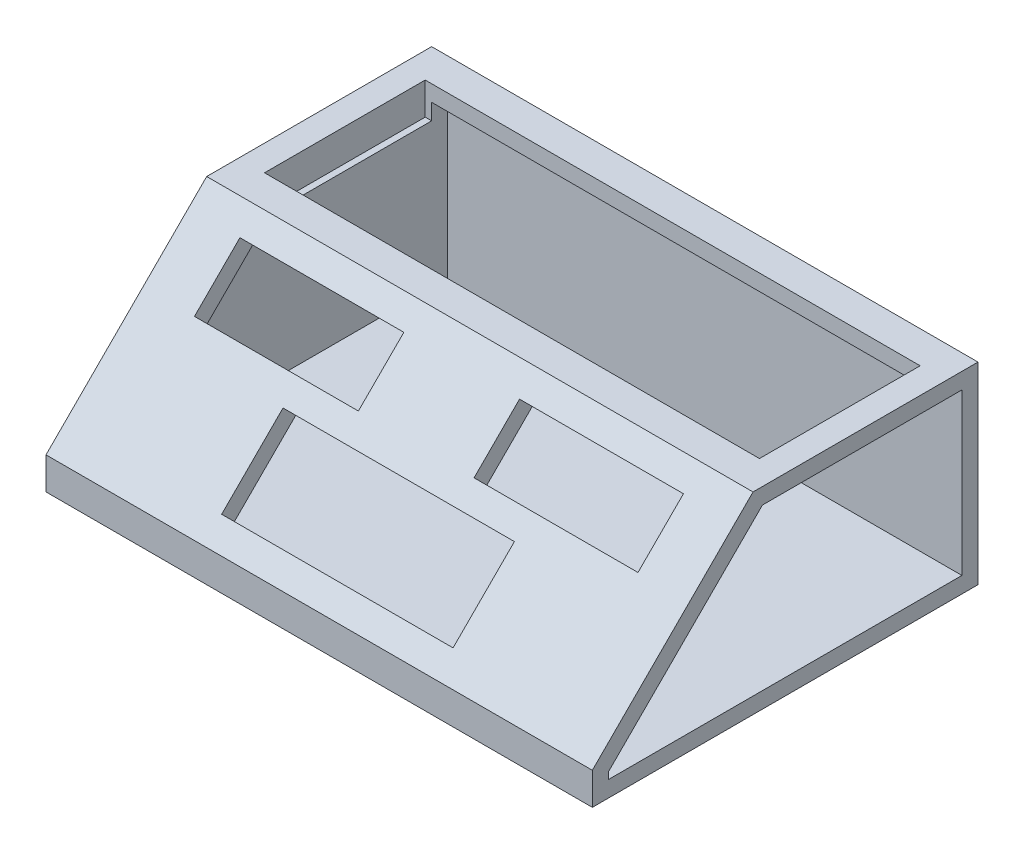
SolidWorks part; units mm, degrees
ref_plane "Front Plane" through (0, 0, 0) normal (0, 0, 1) x (1, 0, 0)
ref_plane "Top Plane" through (0, 0, 0) normal (0, 1, 0) x (1, 0, 0)
ref_plane "Right Plane" through (0, 0, 0) normal (1, 0, 0) x (0, 0, -1)
sketch "Sketch1" plane through (0, 0, 0) normal (1, 0, 0) x (0, 0, -1)
  line L0 (-54.324, 28.1394) -> (15.676, 28.1394)
  line L1 (15.676, 28.1394) -> (15.676, -31.8606)
  line L2 (15.676, -31.8606) -> (-104.324, -31.8606)
  line L3 (-104.324, -31.8606) -> (-104.324, -21.8606)
  line L4 (-104.324, -21.8606) -> (-54.324, 28.1394)
  dimension "D1" = 70
  dimension "D2" = 60
  dimension "D3" = 120
  dimension "D4" = 10
extrude "Boss-Extrude1" add sketch "Sketch1" along normal blind 170
sketch "Sketch2" plane through (0, 28.1394, 0) normal (0, 1, 0) x (1, 0, 0)
  line L0 (0, 15.676) -> (0, -54.324) construction
  line L1 (8, 5.676) -> (162, 5.676)
  line L2 (8, 5.676) -> (8, -44.324)
  line L3 (8, -44.324) -> (162, -44.324)
  line L4 (162, 5.676) -> (162, -44.324)
  line L5 (170, 15.676) -> (0, 15.676) construction
  line L6 (170, -54.324) -> (0, -54.324) construction
  line L7 (170, 15.676) -> (170, -54.324) construction
  dimension "D1" = 8
  dimension "D2" = 10
  dimension "D3" = 10
  dimension "D4" = 8
extrude "Cut-Extrude1" cut sketch "Sketch2" against normal blind 10
sketch "Sketch3" plane through (170, 0, 0) normal (1, 0, 0) x (0, 0, -1)
  line L0 (-51.4024, 23.1394) -> (10.676, 23.1394)
  line L1 (10.676, 23.1394) -> (10.676, -26.8606)
  line L2 (10.676, -26.8606) -> (-99.324, -26.8606)
  line L4 (-104.324, -31.8606) -> (15.676, -31.8606) construction
  line L5 (15.676, -31.8606) -> (15.676, 28.1394) construction
  line L6 (15.676, 28.1394) -> (-54.324, 28.1394) construction
  line L7 (-104.324, -21.8606) -> (-104.324, -31.8606) construction
  line L9 (-51.4024, 23.1394) -> (-99.324, -24.7822)
  line L10 (-99.324, -24.7822) -> (-99.324, -26.8606)
  line L11 (-54.324, 28.1394) -> (-104.324, -21.8606) construction
  dimension "D1" = 5
  dimension "D2" = 5
  dimension "D3" = 5
  dimension "D4" = 5
  dimension "D5" = 5.6014
extrude "Cut-Extrude2" cut sketch "Sketch3" against normal blind 160
sketch "Sketch4" plane through (0, 41.2317, 41.2317) normal (0, 0.7071, 0.7071) x (1, 0, 0)
  line L0 (0, -18.5153) -> (0, -89.226) construction
  line L1 (16, -26.5153) -> (67, -26.5153)
  line L2 (16, -26.5153) -> (16, -46.5153)
  line L3 (16, -46.5153) -> (67, -46.5153)
  line L4 (67, -26.5153) -> (67, -46.5153)
  line L5 (103, -26.5153) -> (154, -26.5153)
  line L6 (103, -26.5153) -> (103, -46.5153)
  line L7 (103, -46.5153) -> (154, -46.5153)
  line L8 (154, -26.5153) -> (154, -46.5153)
  line L9 (49, -54.226) -> (121, -54.226)
  line L10 (49, -54.226) -> (49, -81.226)
  line L11 (49, -81.226) -> (121, -81.226)
  line L12 (121, -54.226) -> (121, -81.226)
  line L13 (170, -18.5153) -> (0, -18.5153) construction
  line L14 (170, -18.5153) -> (170, -89.226) construction
  line L15 (170, -89.226) -> (0, -89.226) construction
  dimension "D1" = 16
  dimension "D2" = 8
  dimension "D3" = 8
  dimension "D4" = 16
  dimension "D5" = 51
  dimension "D6" = 20
  dimension "D7" = 51
  dimension "D8" = 20
  dimension "D9" = 72
  dimension "D10" = 27
  dimension "D11" = 49
  dimension "D12" = 8
extrude "Cut-Extrude3" cut sketch "Sketch4" against normal blind 10
